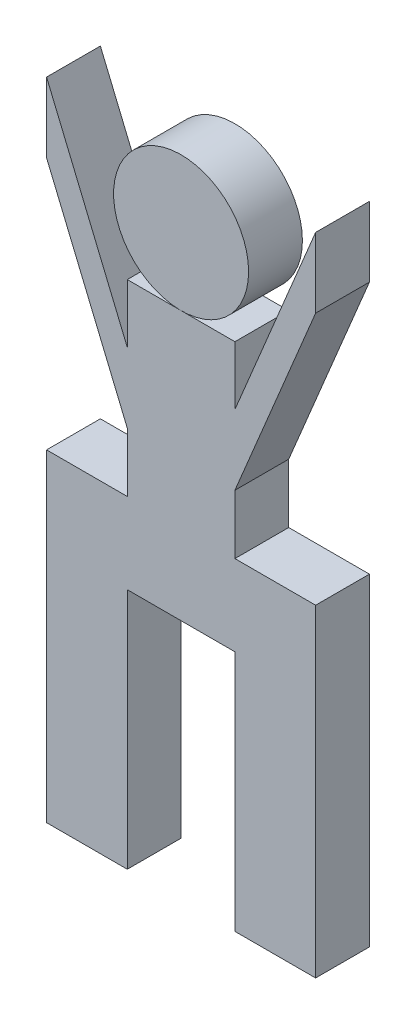
SolidWorks part; units mm, degrees
ref_plane "정면" through (0, 0, 0) normal (0, 0, 1) x (1, 0, 0)
ref_plane "윗면" through (0, 0, 0) normal (0, 1, 0) x (1, 0, 0)
ref_plane "우측면" through (0, 0, 0) normal (1, 0, 0) x (0, 0, -1)
sketch "스케치1" plane through (0, 0, 0) normal (0, 0, 1) x (1, 0, 0)
  line L0 (-25, 0) -> (25, 0)
  line L2 (-25, 60) -> (-25, 47)
  line L3 (-25, -60) -> (25, -60)
  line L4 (25, 60) -> (25, 47)
  line L5 (-25, 60) -> (-10, 24) construction
  line L6 (-10, 24) -> (-10, 34.9107)
  line L8 (-10, -60) -> (10, -60)
  line L9 (-10, -60) -> (-10, -15)
  line L10 (-10, -15) -> (10, -15)
  line L11 (10, -60) -> (10, -15)
  line L13 (-10, -34.9107) -> (-10, 11)
  line L14 (-10, 34.9107) -> (10, 34.9107)
  line L15 (10, -34.9107) -> (10, 11)
  line L16 (10, 24) -> (10, 34.9107)
  line L18 (-10, 24) -> (-25, 60)
  line L19 (10, 24) -> (25, 60)
  line L20 (-25, 47) -> (-10, 11)
  line L21 (25, 47) -> (10, 11)
  line L22 (-25, 0) -> (-25, -60)
  line L23 (25, 0) -> (25, -60)
  line L24 (10, 24) -> (25, 60) construction
  circle A0 centre (0, 47.4554) radius 12.5446
  point P0 (0, 0)
  point P14 (0, 0)
  dimension "D1" = 50
  dimension "D2" = 120
  dimension "D3" = 15
  dimension "D4" = 15
  dimension "D5" = 15
  dimension "D6" = 5
extrude "보스-돌출1" add sketch "스케치1" along normal blind 10 contours A0 | L21 L4 L19 L16 L14 L6 L18 L2 L20 L13 L0 L15 | L0 L22 L3 L9 L13 | L10 L15 L0 L13 | L23 L0 L15 L11 L3
